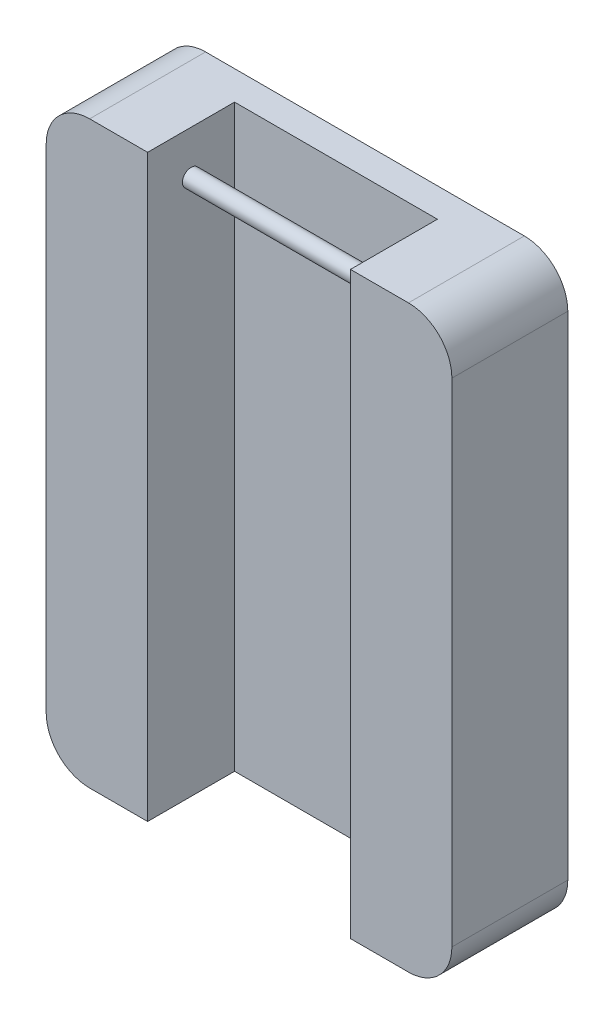
SolidWorks part; units mm, degrees
ref_plane "前视基准面" through (0, 0, 0) normal (0, 0, 1) x (1, 0, 0)
ref_plane "上视基准面" through (0, 0, 0) normal (0, 1, 0) x (1, 0, 0)
ref_plane "右视基准面" through (0, 0, 0) normal (1, 0, 0) x (0, 0, -1)
sketch "草图2" plane through (0, 0, 0) normal (0, 0, 1) x (1, 0, 0)
  line L0 (0, 0) -> (0, 100) construction
  line L1 (0, 100) -> (-55, 100)
  line L2 (-70, 85) -> (-70, -85)
  line L3 (-55, -100) -> (55, -100)
  line L4 (70, -85) -> (70, 85)
  line L5 (55, 100) -> (0, 100)
  arc A1 (-70, 85) -> (-55, 100) centre (-55, 85) cw
  arc A2 (70, 85) -> (55, 100) centre (55, 85) ccw
  arc A3 (55, -100) -> (70, -85) centre (55, -85) ccw
  arc A4 (-70, -85) -> (-55, -100) centre (-55, -85) ccw
  point P10 (-70, 100)
  point P15 (70, -100)
  point P18 (-70, -100)
  dimension "D5" = 15
  dimension "D6" = 15
  dimension "D7" = 15
  dimension "D8" = 15
  dimension "D2" = 70
  dimension "D3" = 200
  dimension "D4" = 140
extrude "凸台-拉伸1" add sketch "草图2" along normal blind 40
sketch "草图3" plane through (0, 0, 40) normal (0, 0, 1) x (1, 0, 0)
  line L0 (0, 100) -> (-35, 100)
  line L6 (55, 100) -> (-55, 100) construction
  line L7 (-35, 100) -> (-35, -100)
  line L8 (-55, -100) -> (55, -100) construction
  line L9 (-35, -100) -> (35, -100)
  line L10 (35, -100) -> (35, 100)
  line L11 (35, 100) -> (0, 100)
  dimension "D1" = 35
  dimension "D2" = 70
extrude "切除-拉伸1" cut sketch "草图3" against normal blind 30
sketch "草图4" plane through (-35, 0, 0) normal (1, 0, 0) x (0, 0, -1)
  line L0 (-10, 100) -> (-10, 85) construction
  line L1 (-10, 100) -> (-40, 100) construction
  line L2 (-10, 100) -> (-10, -100) construction
  line L3 (-10, 85) -> (-25, 85) construction
  circle A0 centre (-25, 85) radius 3
  dimension "D3" = 6
  dimension "D1" = 15
  dimension "D2" = 15
extrude "凸台-拉伸2" add sketch "草图4" along normal blind 83.6501
